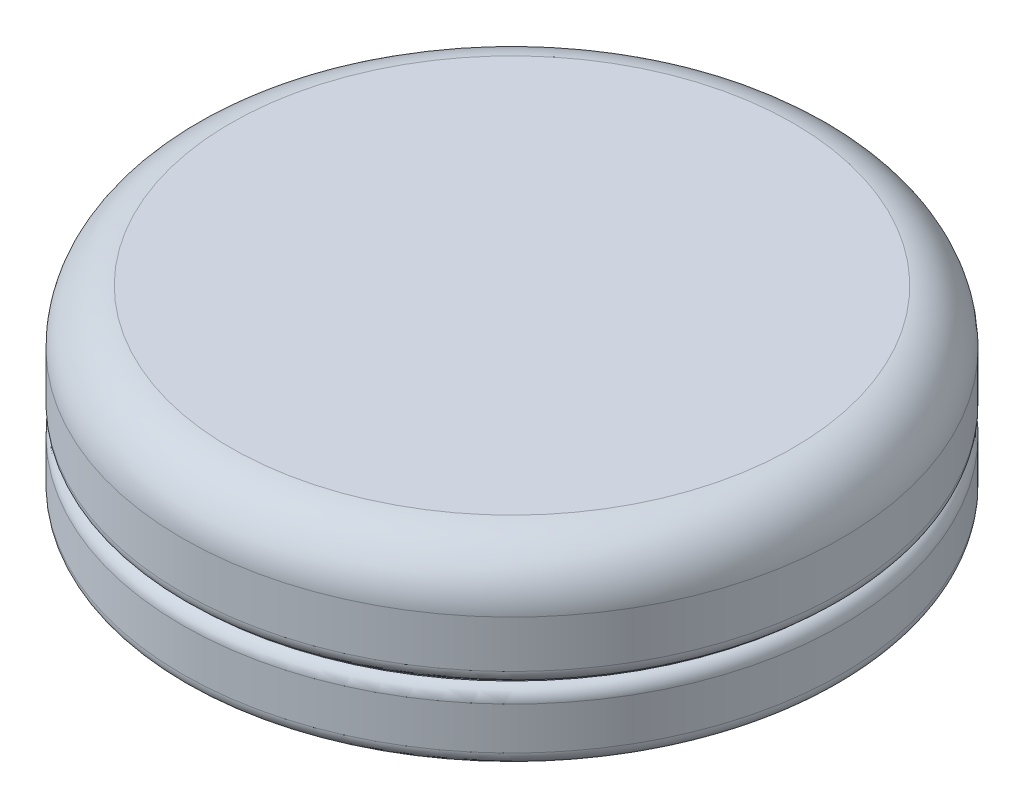
SolidWorks part; units mm, degrees
ref_plane "Front Plane" through (0, 0, 0) normal (0, 0, 1) x (1, 0, 0)
ref_plane "Top Plane" through (0, 0, 0) normal (0, 1, 0) x (1, 0, 0)
ref_plane "Right Plane" through (0, 0, 0) normal (1, 0, 0) x (0, 0, -1)
sketch "Sketch1" plane through (0, 0, 0) normal (0, 0, 1) x (1, 0, 0)
  line L0 (0, 0) -> (0, 95.25) construction
  dimension "D1" = 95.25
sketch "Sketch2" plane through (0, 0, 0) normal (0, 0, 1) x (1, 0, 0)
  line L1 (0, 0) -> (0, 10.0349)
  line L3 (0, 0) -> (-17.018, 0)
  line L4 (-17.78, 0.762) -> (-17.78, 3.048)
  line L5 (-17.78, 4.572) -> (-17.78, 7.112)
  line L8 (170.8832, 3.81) -> (0, 3.81) construction
  line L9 (-17.272, 3.8536) -> (-17.272, 3.7664)
  line L16 (-15.1743, 10.0349) -> (0, 10.0349)
  arc A4 (-15.1743, 10.0349) -> (-17.78, 7.112) centre (-14.8378, 7.112) ccw
  arc A5 (-17.78, 4.572) -> (-17.272, 3.8536) centre (-17.018, 4.572) ccw
  arc A6 (-17.272, 3.7664) -> (-17.78, 3.048) centre (-17.018, 3.048) ccw
  arc A7 (-17.018, 0) -> (-17.78, 0.762) centre (-17.018, 0.762) cw
  dimension "D5" = 0.762
  dimension "D6" = 0.762
  dimension "D13" = 17.78
  dimension "D11" = 3.81
  dimension "D12" = 3.302
  dimension "D14" = 0.508
revolve "Revolve2" add sketch "Sketch2" angle 360 about L1
